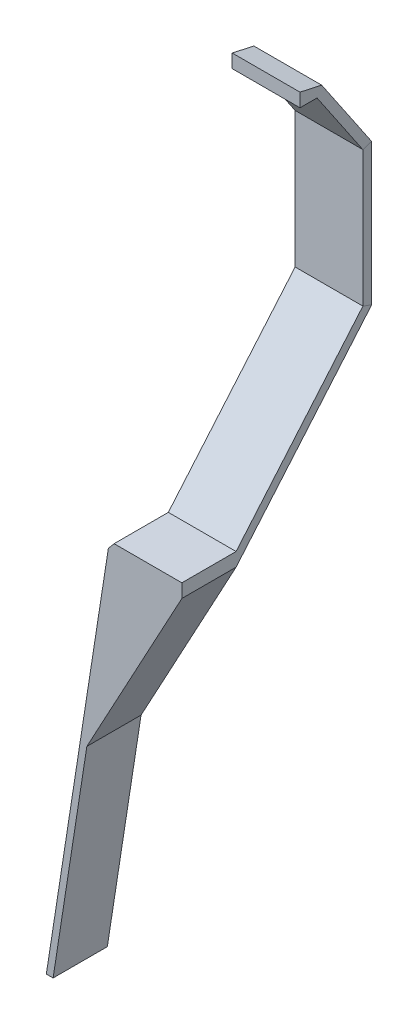
SolidWorks part; units mm, degrees
ref_plane "Front" through (0, 0, 0) normal (0, 0, 1) x (1, 0, 0)
ref_plane "Top" through (0, 0, 0) normal (0, 1, 0) x (1, 0, 0)
ref_plane "Right" through (0, 0, 0) normal (1, 0, 0) x (0, 0, -1)
sketch "草图9" plane through (0, 0, 0) normal (1, 0, 0) x (0, 0, -1)
  line L0 (0, 0) -> (0, 168.8774) construction
  line L1 (-16, 0) -> (16, 0)
  line L2 (-16, 0) -> (-16, 240)
  line L3 (-16, 240) -> (16, 240)
  line L4 (16, 0) -> (16, 240)
  line L5 (0, 0) -> (114.1677, 0) construction
  dimension "D1" = 32
  dimension "D2" = 240
  dimension "D3" = 16
extrude "凸台-拉伸4" add sketch "草图9" along normal blind 8
sketch "草图10" plane through (0, 0, 16) normal (0, 0, 1) x (1, 0, 0)
  line L0 (40, 232) -> (8, 120)
  line L1 (8, 240) -> (40, 240)
  line L2 (8, 240) -> (8, 232)
  line L4 (40, 240) -> (40, 232)
  line L5 (8, 240) -> (8, 0) construction
  line L6 (8, 120) -> (8, 232)
  dimension "D1" = 32
  dimension "D2" = 8
extrude "凸台-拉伸5" add sketch "草图10" against normal blind 32
sketch "草图11" plane through (0, 0, -16) normal (0, 0, -1) x (-1, 0, 0)
  line L0 (0, 0) -> (0, 240) construction
  line L1 (-40, 240) -> (0, 240)
  line L2 (-40, 240) -> (-40, 232)
  line L3 (-40, 232) -> (0, 232)
  line L4 (0, 240) -> (0, 232)
  dimension "D1" = 8
sketch "草图12" plane through (0, 0, 0) normal (-1, 0, 0) x (0, 0, 1)
  line L0 (-16, 240) -> (-90.8392, 328)
  line L1 (-90.8392, 328) -> (-90.8392, 408)
  line L2 (-90.8392, 408) -> (-63.7504, 447.9423)
  line L3 (-63.7504, 447.9423) -> (-53.7048, 447.9423)
  line L4 (-16, 240) -> (16, 240) construction
  point P3 (0, 0)
  point P7 (-62.8366, 451.823)
  point P8 (0, 0)
  point P9 (-53.7048, 447.9423)
  point P11 (-98.0654, 447.9423)
  point P12 (-94.8428, 447.9423)
  point P13 (-63.7504, 447.9423)
  point P14 (-87.1638, 421.248)
  point P15 (-90.8392, 328.5907)
  dimension "D1" = 88
  dimension "D2" = 80
sweep "扫描8" add profiles "草图11" path "草图12"
sketch "草图13" plane through (0, 0, 0) normal (-1, 0, 0) x (0, 0, 1)
  line L0 (-66.4977, 453.1251) -> (-53.7048, 455.9423)
  line L1 (-53.7048, 455.9423) -> (-53.7048, 447.9423)
  line L2 (-53.7048, 447.9423) -> (-63.7504, 447.9423)
  line L3 (-63.7504, 447.9423) -> (-66.4977, 453.1251)
extrude "凸台-拉伸6" add sketch "草图13" against normal blind 40
sketch "草图14" plane through (0, 0, 0) normal (0, -1, 0) x (1, 0, 0)
  line L0 (0, -16) -> (-97.1056, -16) construction
  line L1 (0, 16) -> (-93.3142, 16) construction
  line L2 (0, 16) -> (0, -16) construction
  line L3 (-40, 16) -> (-36, 16)
  line L4 (-40, 16) -> (-40, -16)
  line L5 (-40, -16) -> (-36, -16)
  line L6 (-36, 16) -> (-36, -16)
  dimension "D1" = 4
  dimension "D2" = 36
sketch "草图15" plane through (0, 0, 16) normal (0, 0, 1) x (1, 0, 0)
  line L0 (40, 232) -> (-53.397, 232) construction
  line L1 (-36, 0) -> (0, 232)
  line L2 (-40, 0) -> (-36, 0) construction
  line L3 (-40, 0) -> (-36, 0) construction
  line L4 (0, 232) -> (40, 232)
sweep "扫描9" add profiles "草图14" path "草图15"
sketch "草图16" plane through (0, 0, 16) normal (0, 0, 1) x (1, 0, 0)
  line L1 (0, 232) -> (49.0749, 232)
  line L2 (0, 232) -> (0, -6.2175)
  line L3 (0, -6.2175) -> (49.0749, -6.2175)
  line L4 (49.0749, 232) -> (49.0749, -6.2175)
extrude "切除-拉伸1" cut sketch "草图16" against normal blind 40
sketch "草图17" plane through (0, 0, 16) normal (0, 0, 1) x (1, 0, 0)
  line L0 (-3.3867, 235.9527) -> (0, 240)
  line L1 (0, 240) -> (40, 240)
  line L2 (40, 240) -> (40, 232)
  line L3 (40, 232) -> (-21.6933, 117.9763)
  line L4 (-40, 0) -> (-3.3867, 235.9527) construction
  line L5 (-21.6933, 117.9763) -> (-3.3867, 235.9527)
extrude "凸台-拉伸7" add sketch "草图17" against normal blind 32
